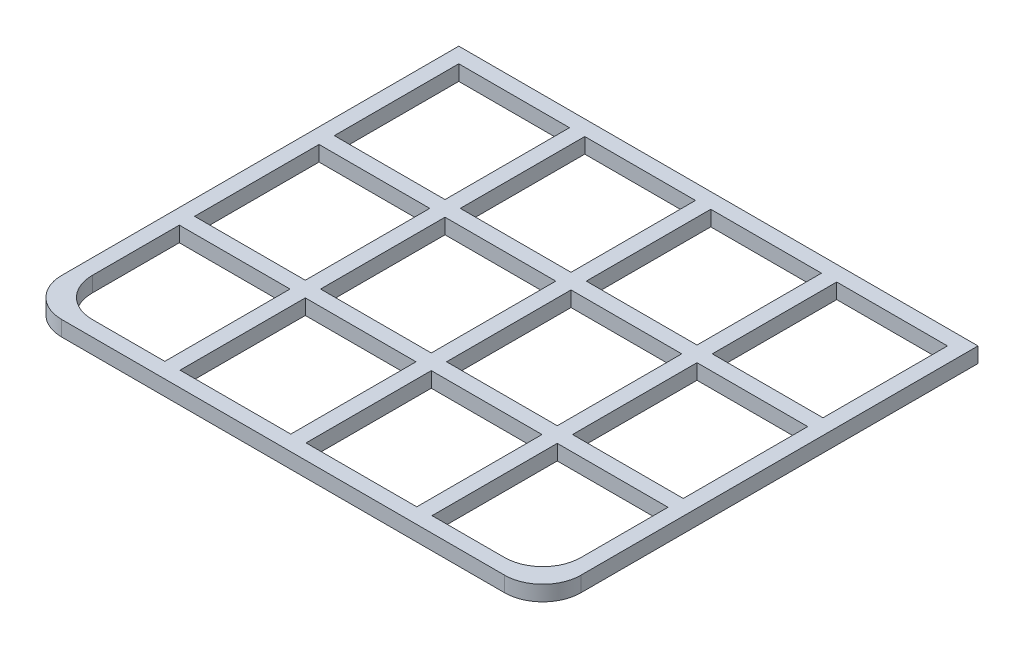
SolidWorks part; units mm, degrees
ref_plane "Front Plane" through (0, 0, 0) normal (0, 0, 1) x (1, 0, 0)
ref_plane "Top Plane" through (0, 0, 0) normal (0, 1, 0) x (1, 0, 0)
ref_plane "Right Plane" through (0, 0, 0) normal (1, 0, 0) x (0, 0, -1)
sketch "Sketch1" plane through (0, 0, 0) normal (0, 1, 0) x (1, 0, 0)
  line L0 (0, 0) -> (-680, 0)
  line L5 (0, 0) -> (0, -520)
  line L6 (-680, 0) -> (-680, -520)
  line L7 (-50, -570) -> (-630, -570)
  line L8 (-515, -203) -> (-515, -366)
  line L9 (-20, -20) -> (-165, -20)
  line L10 (-20, -20) -> (-20, -183)
  line L11 (-70, -550) -> (-165, -550)
  line L12 (-660, -20) -> (-660, -183)
  line L17 (-660, -183) -> (-515, -183)
  line L19 (-660, -203) -> (-515, -203)
  line L21 (-660, -366) -> (-515, -366)
  line L23 (-660, -386) -> (-515, -386)
  line L26 (-515, -20) -> (-515, -183)
  line L28 (-495, -20) -> (-495, -183)
  line L30 (-350, -20) -> (-350, -183)
  line L32 (-330, -20) -> (-330, -183)
  line L34 (-185, -20) -> (-185, -183)
  line L36 (-165, -20) -> (-165, -183)
  line L37 (-495, -183) -> (-350, -183)
  line L38 (-495, -203) -> (-495, -366)
  line L39 (-495, -203) -> (-350, -203)
  line L40 (-660, -203) -> (-660, -366)
  line L41 (-330, -203) -> (-330, -366)
  line L42 (-350, -203) -> (-350, -366)
  line L43 (-330, -183) -> (-185, -183)
  line L44 (-330, -203) -> (-185, -203)
  line L45 (-165, -203) -> (-165, -366)
  line L46 (-185, -203) -> (-185, -366)
  line L47 (-165, -183) -> (-20, -183)
  line L48 (-165, -203) -> (-20, -203)
  line L49 (-20, -203) -> (-20, -366)
  line L50 (-660, -386) -> (-660, -500)
  line L51 (-515, -386) -> (-515, -550)
  line L52 (-495, -386) -> (-495, -550)
  line L53 (-350, -386) -> (-350, -550)
  line L54 (-330, -386) -> (-330, -550)
  line L55 (-185, -386) -> (-185, -550)
  line L56 (-165, -386) -> (-165, -550)
  line L57 (-20, -386) -> (-20, -500)
  line L58 (-495, -366) -> (-350, -366)
  line L59 (-495, -386) -> (-350, -386)
  line L60 (-330, -366) -> (-185, -366)
  line L61 (-330, -386) -> (-185, -386)
  line L62 (-165, -366) -> (-20, -366)
  line L63 (-165, -386) -> (-20, -386)
  line L64 (-515, -20) -> (-660, -20)
  line L65 (-350, -20) -> (-495, -20)
  line L66 (-185, -20) -> (-330, -20)
  line L67 (-515, -550) -> (-610, -550)
  line L68 (-350, -550) -> (-495, -550)
  line L69 (-185, -550) -> (-330, -550)
  arc A0 (-610, -550) -> (-660, -500) centre (-610, -500) cw
  arc A1 (-20, -500) -> (-70, -550) centre (-70, -500) cw
  arc A2 (-630, -570) -> (-680, -520) centre (-630, -520) cw
  arc A3 (-50, -570) -> (0, -520) centre (-50, -520) ccw
  point P19 (-680, -570)
  dimension "D7" = 50
  dimension "D8" = 50
  dimension "D9" = 50
  dimension "D10" = 50
  dimension "D1" = 680
  dimension "D2" = 570
  dimension "D3" = 20
  dimension "D4" = 20
  dimension "D5" = 20
  dimension "D6" = 20
  dimension "D11" = 20
  dimension "D12" = 20
  dimension "D13" = 20
  dimension "D14" = 20
  dimension "D15" = 20
  dimension "D16" = 330
  dimension "D17" = 145
  dimension "D18" = 145
  dimension "D19" = 163
  dimension "D20" = 163
extrude "baga" add sketch "Sketch1" along normal blind 20
